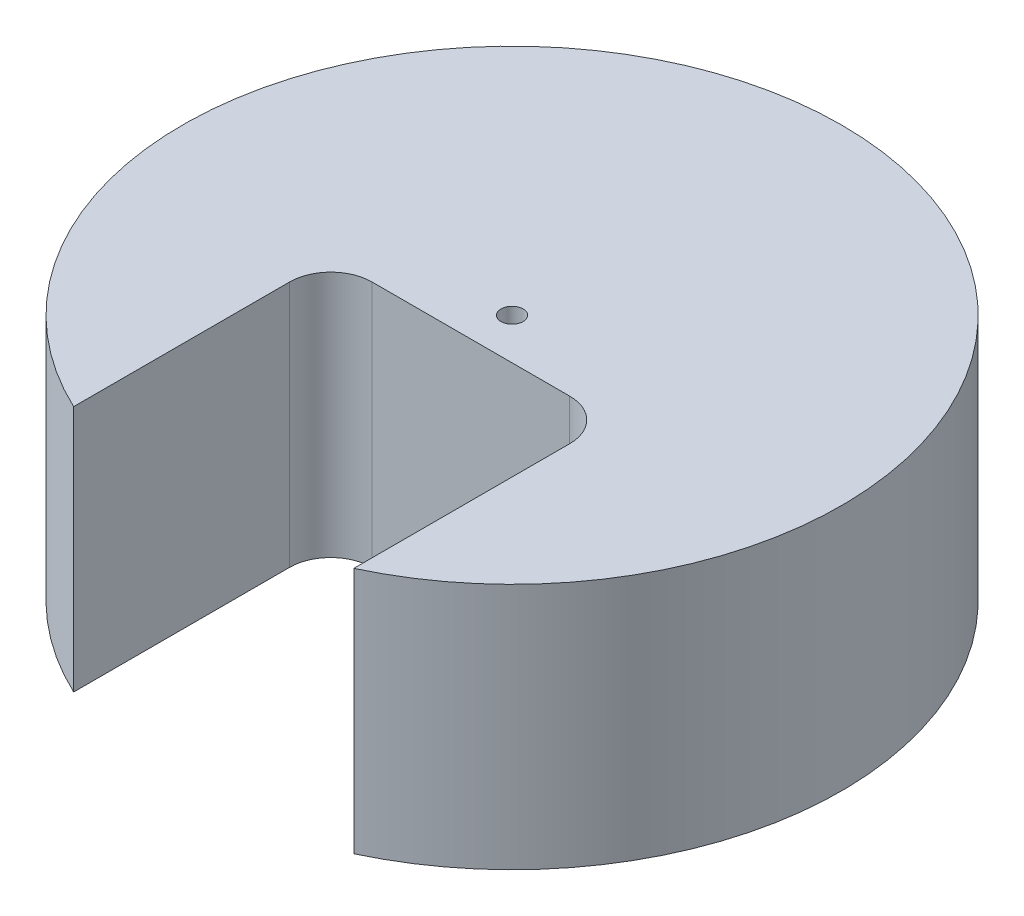
SolidWorks part; units mm, degrees
ref_plane "Front Plane" through (0, 0, 0) normal (0, 0, 1) x (1, 0, 0)
ref_plane "Top Plane" through (0, 0, 0) normal (0, 1, 0) x (1, 0, 0)
ref_plane "Right Plane" through (0, 0, 0) normal (1, 0, 0) x (0, 0, -1)
sketch "Sketch1" plane through (0, 0, 0) normal (0, 1, 0) x (1, 0, 0)
  circle A0 centre (0, 0) radius 50.8
  dimension "D1" = 101.6
extrude "Boss-Extrude1" add sketch "Sketch1" along normal blind 38.1
sketch "Sketch2" plane through (0, 38.1, 0) normal (0, 1, 0) x (1, 0, 0)
  line L1 (-21.59, -6.35) -> (21.59, -6.35)
  line L2 (-21.59, -6.35) -> (-21.59, -50.8)
  line L3 (-21.59, -50.8) -> (21.59, -50.8)
  line L4 (21.59, -6.35) -> (21.59, -50.8)
  circle A1 centre (0, 0) radius 50.8 construction
  point P7 (0, -6.35)
  dimension "D1" = 6.35
  dimension "D2" = 43.18
extrude "Cut-Extrude1" cut sketch "Sketch2" against normal up to next
fillet "Fillet1" radius 6.35 2 edges at (21.59, 19.05, 6.35) (-21.59, 19.05, 6.35)
hole_wizard "M3 Clearance Hole1" positions "Sketch4" profile "Sketch5" hole size "M3" standard "ANSI Metric" end condition through all
sketch "Sketch4" plane through (0, 38.1, 0) normal (0, 1, 0) x (1, 0, 0)
  point P0 (0, 0)
sketch "Sketch5" plane through (0, 38.1, 0) normal (1, 0, 0) x (0, 0, 1)
  line L0 (0, 0) -> (0, 38.1)
  line L1 (0, 38.1) -> (1.7, 38.1)
  line L2 (1.7, 38.1) -> (1.7, 0)
  line L5 (1.7, 0) -> (0, 0)
  line L11 (0, -6.35) -> (0, 107.95) construction
  dimension "Thru Hole Dia." = 3.4
  dimension "Thru Hole Depth" = 38.1
